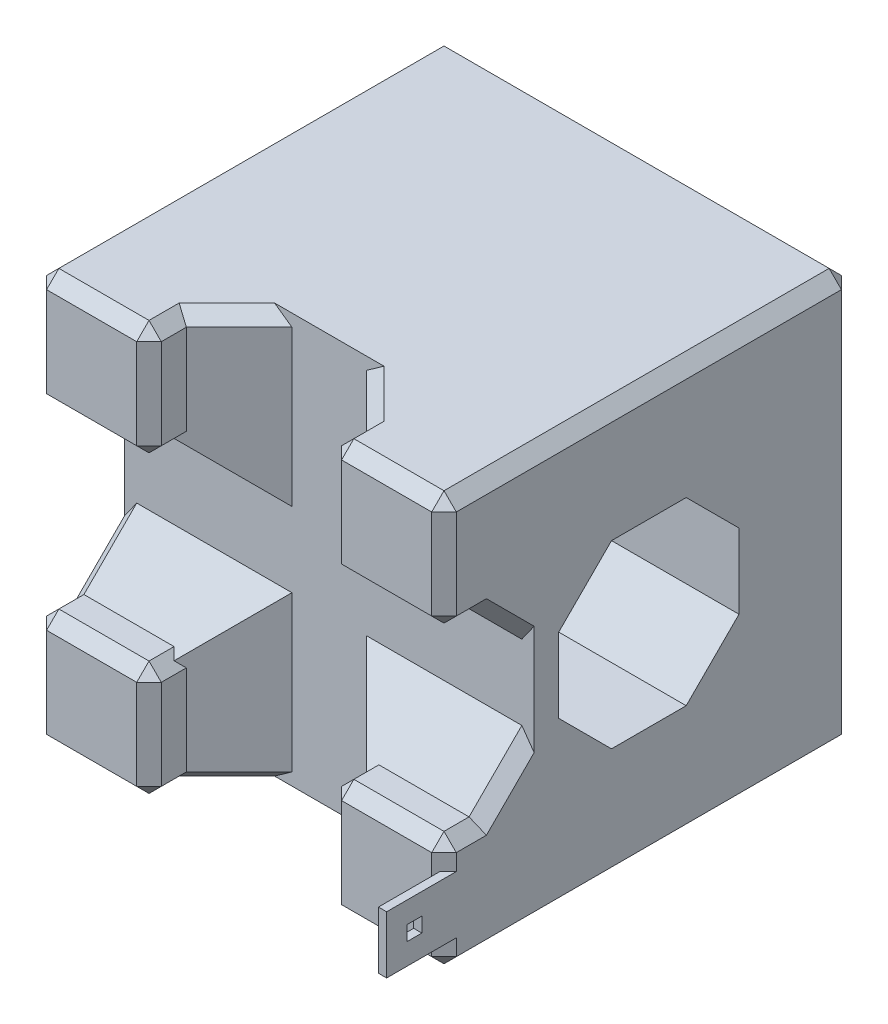
SolidWorks part; units mm, degrees
ref_plane "Front" through (0, 0, 0) normal (0, 0, 1) x (1, 0, 0)
ref_plane "Top" through (0, 0, 0) normal (0, 1, 0) x (1, 0, 0)
ref_plane "Right" through (0, 0, 0) normal (1, 0, 0) x (0, 0, -1)
sketch "Sketch1" plane through (0, 0, 0) normal (0, 0, 1) x (1, 0, 0)
  line L1 (0, 0) -> (50, 0)
  line L2 (0, 0) -> (0, 50)
  line L3 (0, 50) -> (50, 50)
  line L4 (50, 0) -> (50, 50)
  dimension "D1" = 50
extrude "Boss-Extrude1" add sketch "Sketch1" along normal blind 50
sketch "Sketch2" plane through (0, 0, 0) normal (-1, 0, 0) x (0, 0, 1)
  line L0 (25, 25) -> (25, 50) construction
  line L1 (39, 36) -> (61, 36) construction
  line L2 (39, 36) -> (39, 14) construction
  line L3 (39, 14) -> (61, 14) construction
  line L4 (61, 36) -> (61, 14) construction
  line L5 (39, 36) -> (61, 14) construction
  line L6 (39, 14) -> (61, 36) construction
  line L7 (50, 50) -> (0, 50) construction
  line L8 (50, 50) -> (50, 0) construction
  line L10 (14, 36) -> (36, 36) construction
  line L11 (14, 36) -> (14, 14) construction
  line L12 (14, 14) -> (36, 14) construction
  line L13 (36, 36) -> (36, 14) construction
  line L14 (36, 29.5563) -> (29.5563, 36)
  line L15 (14, 36) -> (36, 14) construction
  line L16 (29.5563, 36) -> (20.4437, 36)
  line L17 (14, 14) -> (36, 36) construction
  line L18 (61, 29.5563) -> (54.5563, 36)
  line L19 (54.5563, 36) -> (45.4437, 36)
  line L20 (45.4437, 36) -> (39, 29.5563)
  line L21 (39, 29.5563) -> (39, 20.4437)
  line L22 (39, 20.4437) -> (45.4437, 14)
  line L23 (45.4437, 14) -> (54.5563, 14)
  line L24 (54.5563, 14) -> (61, 20.4437)
  line L25 (61, 20.4437) -> (61, 29.5563)
  line L26 (20.4437, 36) -> (14, 29.5563)
  line L27 (14, 29.5563) -> (14, 20.4437)
  line L28 (14, 20.4437) -> (20.4437, 14)
  line L29 (20.4437, 14) -> (29.5563, 14)
  line L30 (29.5563, 14) -> (36, 20.4437)
  line L31 (36, 20.4437) -> (36, 29.5563)
  circle A0 centre (50, 25) radius 11 construction
  circle A1 centre (25, 25) radius 11 construction
  point P0 (50, 25)
  point P5 (25, 25)
  dimension "D1" = 22
extrude "Cut-Extrude1" cut sketch "Sketch2" against normal through all
sketch "Sketch3" plane through (0, 0, 0) normal (0, -1, 0) x (1, 0, 0)
  line L0 (0, 50) -> (50, 50) construction
  line L7 (14, 61) -> (36, 61) construction
  line L8 (14, 61) -> (14, 39) construction
  line L9 (14, 39) -> (36, 39) construction
  line L10 (36, 61) -> (36, 39) construction
  line L11 (14, 61) -> (36, 39) construction
  line L12 (14, 39) -> (36, 61) construction
  line L16 (29.5563, 39) -> (36, 45.4437)
  line L17 (36, 45.4437) -> (36, 54.5563)
  line L18 (36, 54.5563) -> (29.5563, 61)
  line L19 (29.5563, 61) -> (20.4437, 61)
  line L20 (20.4437, 61) -> (14, 54.5563)
  line L21 (14, 54.5563) -> (14, 45.4437)
  line L22 (14, 45.4437) -> (20.4437, 39)
  line L23 (20.4437, 39) -> (29.5563, 39)
  circle A0 centre (25, 50) radius 11 construction
  point P5 (25, 50)
  dimension "D1" = 22
extrude "Cut-Extrude2" cut sketch "Sketch3" against normal through all
chamfer "Chamfer1" distance 1.5 angle 45 44 edges at (14, 14, 47.7218) (14, 50, 47.7218) (25, 50, 0) (36, 36, 47.7218) (36, 43, 50) (36, 50, 47.7218) (43, 50, 50) (43, 36, 50) (50, 36, 47.7218) (50, 43, 50) (50, 50, 25) (50, 25, 0) (36, 0, 47.7218) (36, 14, 47.7218) (43, 14, 50) (36, 7, 50) (43, 0, 50) (50, 7, 50) (50, 0, 25) (25, 0, 0) (0, 43, 50) (0, 36, 47.7218) (7, 36, 50) (14, 36, 47.7218) (14, 43, 50) (7, 50, 50) (0, 50, 25) (0, 25, 0) (0, 14, 47.7218) (0, 7, 50) (7, 14, 50) (14, 7, 50) (14, 0, 47.7218) (7, 0, 50) (0, 0, 25) (50, 14, 47.7218) (0, 17.2218, 42.2218) (0, 32.7782, 42.2218) (50, 32.7782, 42.2218) (50, 17.2218, 42.2218) (17.2218, 0, 42.2218) (32.7782, 0, 42.2218) (17.2218, 50, 42.2218) (32.7782, 50, 42.2218)
sketch "Sketch4" plane through (0, 0, 50) normal (0, 0, 1) x (1, 0, 0)
  line L0 (50, 12.5) -> (50, 1.5) construction
  line L1 (50, 10.5) -> (49, 10.5)
  line L2 (50, 10.5) -> (50, 3.5)
  line L3 (50, 3.5) -> (49, 3.5)
  line L4 (49, 10.5) -> (49, 3.5)
  point P6 (50, 7)
  dimension "D1" = 1
  dimension "D2" = 7
extrude "Boss-Extrude2" add sketch "Sketch4" along normal blind 7 and the other way blind 10
sketch "Sketch5" plane through (50, 0, 0) normal (1, 0, 0) x (0, 0, -1)
  line L0 (-54.5, 7) -> (-57, 7) construction
  line L1 (-54.5, 6.1) -> (-52.7, 6.1)
  line L2 (-54.5, 6.1) -> (-54.5, 7.9)
  line L3 (-54.5, 7.9) -> (-52.7, 7.9)
  line L4 (-52.7, 6.1) -> (-52.7, 7.9)
  line L5 (-57, 3.5) -> (-57, 10.5) construction
  dimension "D1" = 2.5
  dimension "D2" = 1.8
extrude "Cut-Extrude3" cut sketch "Sketch5" against normal blind 7
